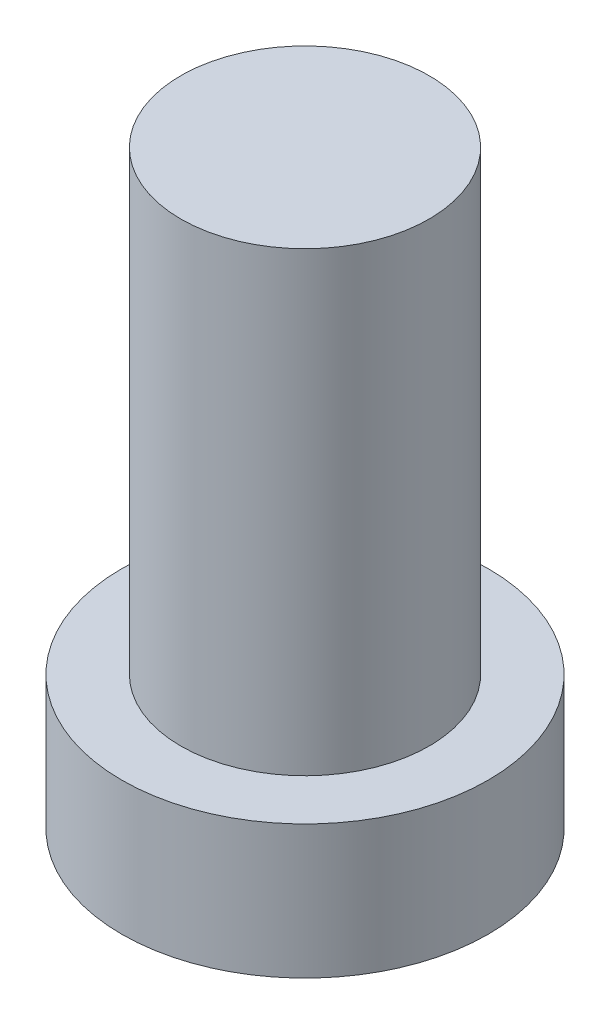
SolidWorks part; units mm, degrees
ref_plane "Front Plane" through (0, 0, 0) normal (0, 0, 1) x (1, 0, 0)
ref_plane "Top Plane" through (0, 0, 0) normal (0, 1, 0) x (1, 0, 0)
ref_plane "Right Plane" through (0, 0, 0) normal (1, 0, 0) x (0, 0, -1)
other "Configuration Table"
sketch "草图1" plane through (0, 0, 0) normal (0, 1, 0) x (1, 0, 0)
  circle A0 centre (0, 0) radius 5.9
extrude "凸台-拉伸1" add sketch "草图1" along normal blind 4.3
sketch "草图2" plane through (0, 4.3, 0) normal (0, 1, 0) x (1, 0, 0)
  circle A0 centre (0, 0) radius 4
extrude "凸台-拉伸2" add sketch "草图2" along normal blind 14.7
